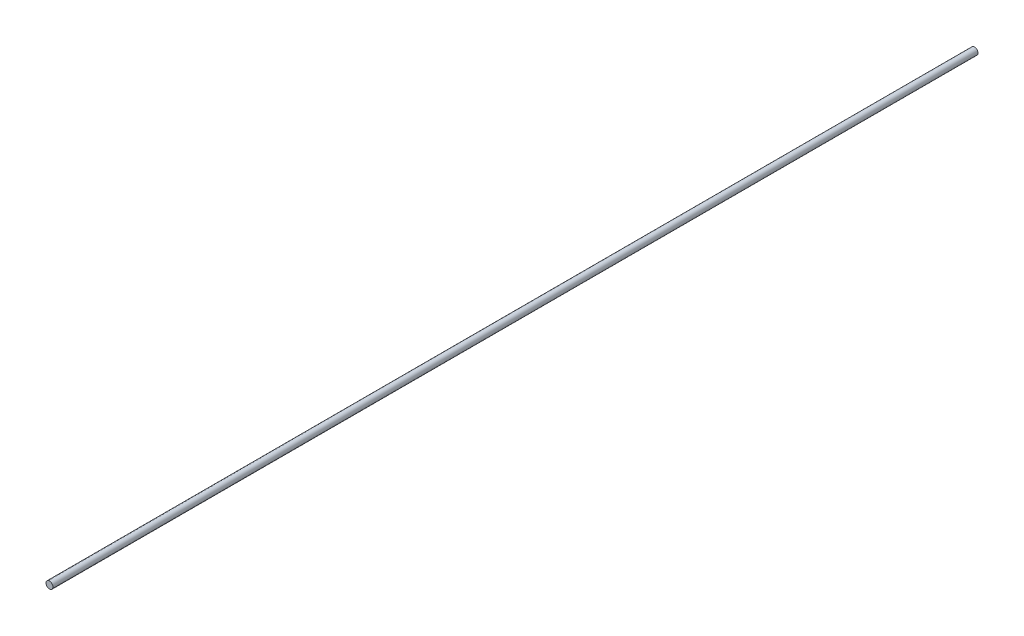
SolidWorks part; units mm, degrees
material "Titanium Ti-8Mn, Annealed"
ref_plane "Front" through (0, 0, 0) normal (0, 0, 1) x (1, 0, 0)
ref_plane "Top" through (0, 0, 0) normal (0, 1, 0) x (1, 0, 0)
ref_plane "Right" through (0, 0, 0) normal (1, 0, 0) x (0, 0, -1)
sketch "BackboneSke" plane through (0, 0, 0) normal (0, 0, 1) x (1, 0, 0)
  circle A0 centre (0, 0) radius 0.75
  dimension "D1" = 1.5
extrude "Backbone" add sketch "BackboneSke" along normal blind 200
